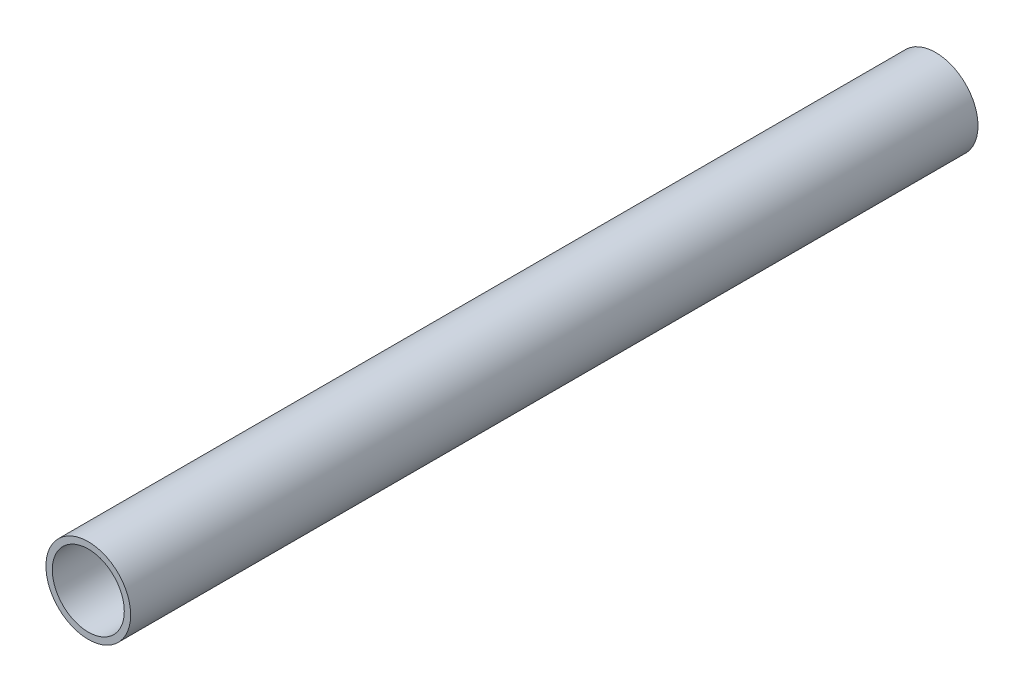
SolidWorks part; units mm, degrees
ref_plane "Спереди" through (0, 0, 0) normal (0, 0, 1) x (1, 0, 0)
ref_plane "Сверху" through (0, 0, 0) normal (0, 1, 0) x (1, 0, 0)
ref_plane "Справа" through (0, 0, 0) normal (1, 0, 0) x (0, 0, -1)
sketch "Эскиз1" plane through (0, 0, 0) normal (0, 0, 1) x (1, 0, 0)
  circle A0 centre (0, 0) radius 10
  circle A1 centre (0, 0) radius 8.5
extrude "Бобышка-Вытянуть1" add sketch "Эскиз1" along normal blind 200
